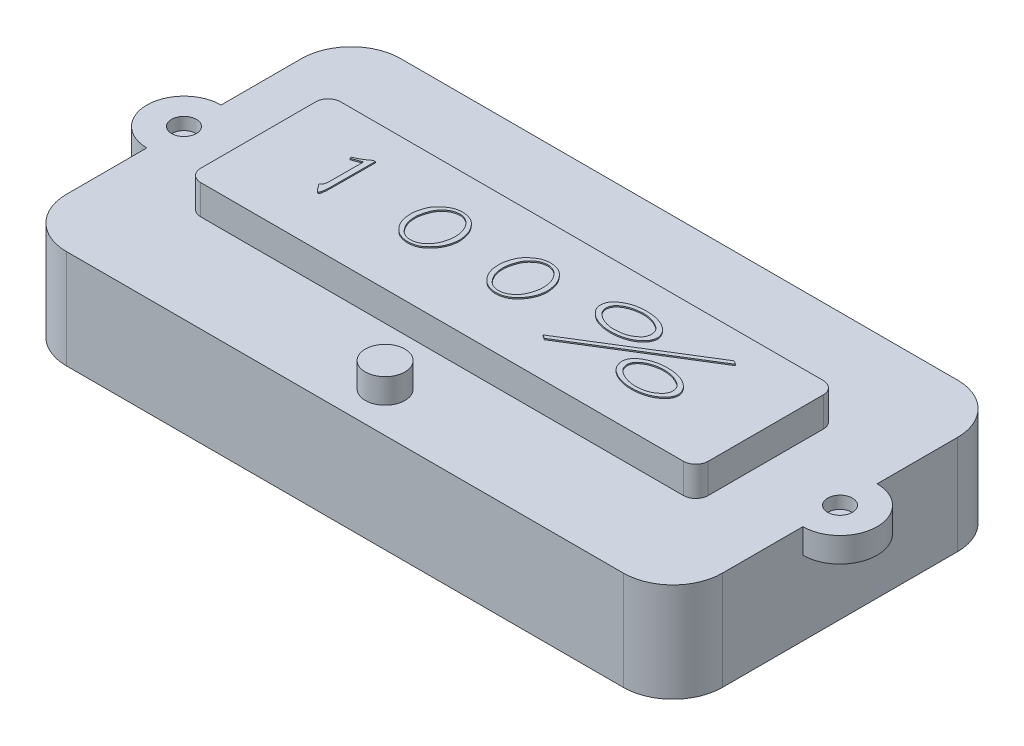
SolidWorks part; units mm, degrees
ref_plane "前视基准面" through (0, 0, 0) normal (0, 0, 1) x (1, 0, 0)
ref_plane "上视基准面" through (0, 0, 0) normal (0, 1, 0) x (1, 0, 0)
ref_plane "右视基准面" through (0, 0, 0) normal (1, 0, 0) x (0, 0, -1)
sketch "草图1" plane through (0, 0, 0) normal (0, 1, 0) x (1, 0, 0)
  line L1 (26.5, -13.5) -> (-26.5, -13.5)
  line L2 (26.5, -13.5) -> (26.5, 13.5)
  line L3 (26.5, 13.5) -> (-26.5, 13.5)
  line L4 (-26.5, -13.5) -> (-26.5, 13.5)
  line L5 (26.5, -13.5) -> (-26.5, 13.5) construction
  line L6 (26.5, 13.5) -> (-26.5, -13.5) construction
  point P0 (0, 0)
  dimension "D1" = 53
  dimension "D2" = 27
extrude "凸台-拉伸1" add sketch "草图1" along normal blind 8
sketch "草图2" plane through (0, 8, 0) normal (0, 1, 0) x (1, 0, 0)
  line L1 (20.5, -5.65) -> (-20.5, -5.65)
  line L2 (20.5, -5.65) -> (20.5, 5.65)
  line L3 (20.5, 5.65) -> (-20.5, 5.65)
  line L4 (-20.5, -5.65) -> (-20.5, 5.65)
  line L5 (20.5, -5.65) -> (-20.5, 5.65) construction
  line L6 (20.5, 5.65) -> (-20.5, -5.65) construction
  point P0 (0, 0)
  dimension "D1" = 41
  dimension "D2" = 11.3
extrude "凸台-拉伸2" add sketch "草图2" along normal blind 2.4
sketch "草图3" plane through (0, 0, 0) normal (0, -1, 0) x (1, 0, 0)
  line L1 (-18.8905, -9.1564) -> (-7.3367, -9.1564)
  line L2 (-18.8905, -9.1564) -> (-18.8905, -4.997)
  line L3 (-18.8905, -4.997) -> (-7.3367, -4.997)
  line L4 (-7.3367, -9.1564) -> (-7.3367, -4.997)
  line L5 (-18.8905, -9.1564) -> (-7.3367, -4.997) construction
  line L6 (-18.8905, -4.997) -> (-7.3367, -9.1564) construction
  point P0 (-13.1136, -7.0767)
extrude "凸台-拉伸3" add sketch "草图3" along normal blind 7
sketch "草图4" plane through (0, 8, 0) normal (0, 1, 0) x (1, 0, 0)
  line L0 (0, 0) -> (0, 4.9393) construction
  circle A2 centre (-26.5, 0) radius 3
  circle A3 centre (26.5, 0) radius 3
  dimension "D3" = 59
  dimension "D4" = 6
  dimension "D1" = 53
extrude "凸台-拉伸4" add sketch "草图4" against normal blind 2
sketch "草图5" plane through (0, 8, 0) normal (0, 1, 0) x (1, 0, 0)
  line L0 (0, 0) -> (0, 5.1964) construction
  circle A0 centre (-26.5, 0) radius 1
  circle A1 centre (26.5, 0) radius 1
  dimension "D1" = 2
extrude "切除-拉伸1" cut sketch "草图5" against normal blind 1
fillet "圆角1" radius 4 4 edges at (26.5, 4, -13.5) (26.5, 4, 13.5) (-26.5, 4, 13.5) (-26.5, 4, -13.5)
fillet "圆角2" radius 1 4 edges at (20.5, 9.2, 5.65) (20.5, 9.2, -5.65) (-20.5, 9.2, 5.65) (-20.5, 9.2, -5.65)
sketch "草图6" plane through (0, 10.4, 0) normal (0, 1, 0) x (1, 0, 0)
  text T0 "100%" font "汉仪长仿宋体" height in points 18
extrude "凸台-拉伸5" add sketch "草图6" along normal blind 0.1
sketch "草图7" plane through (0, 8, 0) normal (0, 1, 0) x (1, 0, 0)
  line L0 (-19.5, -5.65) -> (19.5, -5.65) construction
  circle A0 centre (0, -10.25) radius 1.6
  point P2 (0, 0)
  dimension "D1" = 3.2
  dimension "D2" = 4.6
extrude "凸台-拉伸6" add sketch "草图7" along normal blind 2
